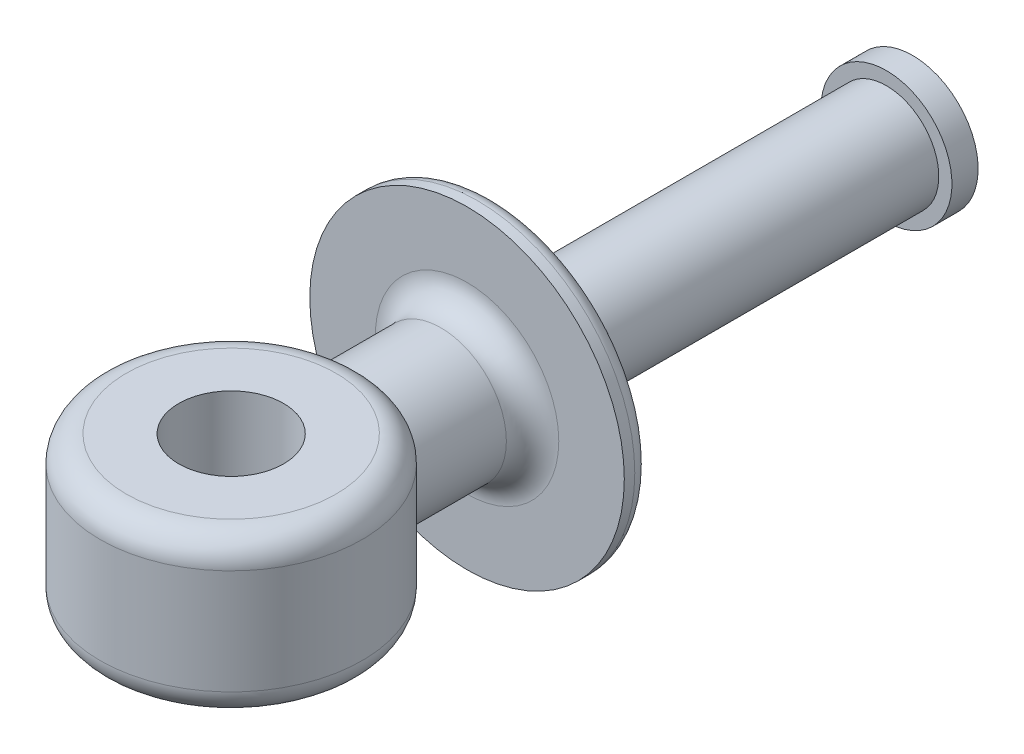
SolidWorks part; units mm, degrees
ref_plane "前视基准面" through (0, 0, 0) normal (0, 0, 1) x (1, 0, 0)
ref_plane "上视基准面" through (0, 0, 0) normal (0, 1, 0) x (1, 0, 0)
ref_plane "右视基准面" through (0, 0, 0) normal (1, 0, 0) x (0, 0, -1)
sketch "草图1" plane through (0, 0, 0) normal (0, 0, 1) x (1, 0, 0)
  circle A0 centre (0, 0) radius 10
  dimension "D1" = 20
extrude "凸台-拉伸1" add sketch "草图1" along normal blind 75
sketch "草图2" plane through (0, 0, 0) normal (0, 0, -1) x (-1, 0, 0)
  circle A0 centre (0, 0) radius 12.5
  dimension "D1" = 25
extrude "凸台-拉伸2" add sketch "草图2" along normal blind 5
sketch "草图3" plane through (0, 0, 75) normal (0, 0, 1) x (1, 0, 0)
  circle A0 centre (0, 0) radius 30
  dimension "D1" = 60
extrude "凸台-拉伸3" add sketch "草图3" along normal blind 5
sketch "草图4" plane through (0, 0, 80) normal (0, 0, 1) x (1, 0, 0)
  circle A0 centre (0, 0) radius 12.5
  dimension "D1" = 25
extrude "凸台-拉伸4" add sketch "草图4" along normal blind 30
sketch "草图5" plane through (0, 0, 0) normal (0, 1, 0) x (1, 0, 0)
  line L1 (-12.5, -110) -> (12.5, -110) construction
  circle A0 centre (0, -125) radius 25
  dimension "D1" = 15
  dimension "D2" = 50
extrude "凸台-拉伸5" add sketch "草图5" along normal mid plane 30 separate body contours A0
sketch "草图6" plane through (0, 15, 0) normal (0, 1, 0) x (1, 0, 0)
  circle A0 centre (0, -125) radius 10
  dimension "D1" = 20
extrude "切除-拉伸1" cut sketch "草图6" against normal through all
fillet "圆角1" radius 5 1 edges at (12.5, 0, 80)
fillet "圆角2" radius 5 2 edges at (0, -15, 150) (0, 15, 150)
fillet "圆角4" radius 3 1 edges at (30, 0, 75)
scale "缩放比例1" bodies to scale 111 109 scale about origin uniform scaling yes scale factor 0.5
